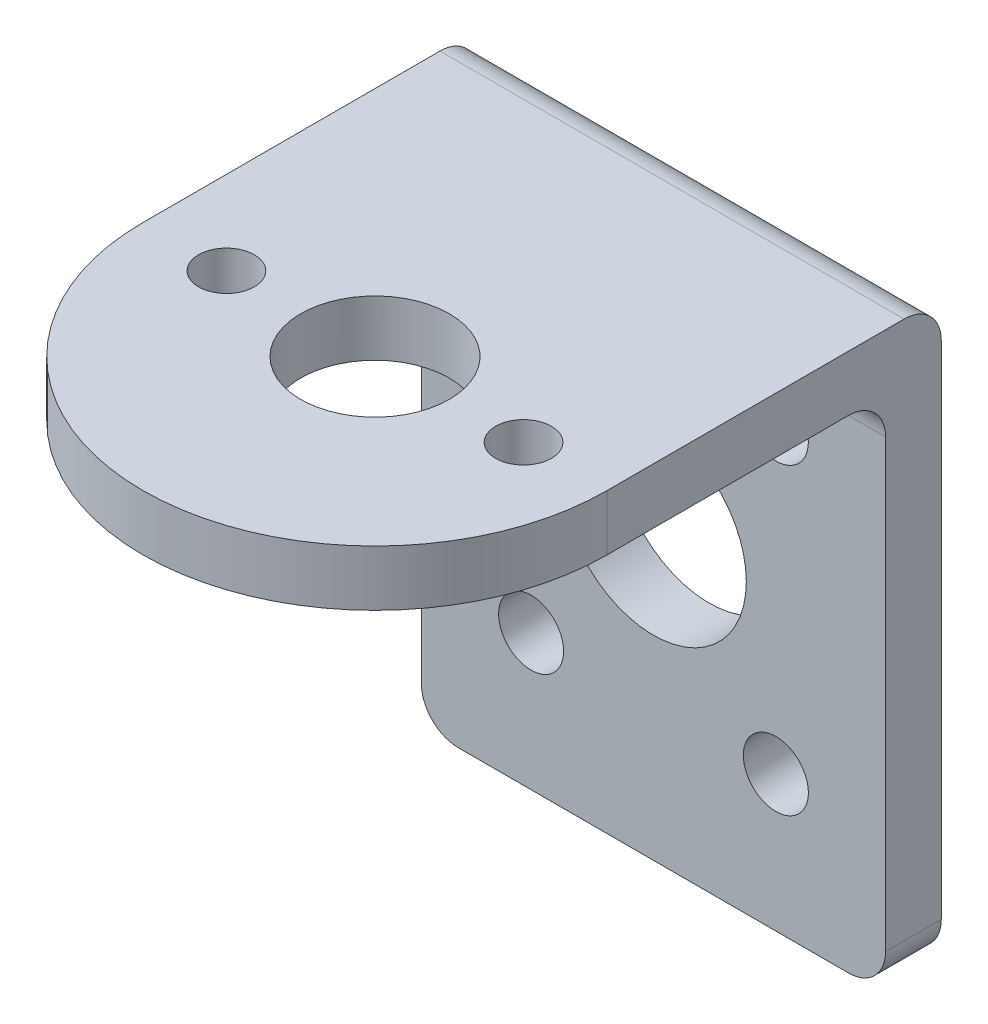
SolidWorks part; units mm, degrees
material "AISI 1020"
ref_plane "Plan de face" through (0, 0, 0) normal (0, 0, 1) x (1, 0, 0)
ref_plane "Plan de dessus" through (0, 0, 0) normal (0, 1, 0) x (1, 0, 0)
ref_plane "Plan de droite" through (0, 0, 0) normal (1, 0, 0) x (0, 0, -1)
sketch "Esquisse1" plane through (0, 0, 0) normal (0, 0, 1) x (1, 0, 0)
  line L0 (25, 15.4244) -> (0, -15.5756) construction
  line L1 (0, 15.4244) -> (25, 15.4244)
  line L2 (0, 15.4244) -> (0, -15.5756)
  line L3 (0, -15.5756) -> (25, -15.5756)
  line L4 (25, 15.4244) -> (25, -15.5756)
  line L5 (12.5, -0.0756) -> (12.5, 15.4244) construction
  line L6 (12.5, -0.0756) -> (0, -0.0756) construction
  circle A0 centre (12.5, -0.0756) radius 5
  circle A1 centre (19.0914, 8.0977) radius 1.75
  circle A2 centre (5.9086, 8.0977) radius 1.75
  circle A3 centre (19.0914, -8.249) radius 1.75
  circle A4 centre (5.9086, -8.249) radius 1.75
  dimension "D3" = 10
  dimension "D4" = 3.5
  dimension "D1" = 25
  dimension "D2" = 31
  dimension "D5" = 10.5
extrude "Boss.-Extru.1" add sketch "Esquisse1" along normal blind 3
sketch "Esquisse2" plane through (0, 0, 3) normal (0, 0, 1) x (1, 0, 0)
  line L0 (25, 15.4244) -> (0, 15.4244) construction
  line L1 (0, 15.4244) -> (25, 15.4244)
  line L2 (0, 15.4244) -> (0, 12.4244)
  line L3 (0, 12.4244) -> (25, 12.4244)
  line L4 (25, 15.4244) -> (25, 12.4244)
  line L5 (0, 15.4244) -> (0, -15.5756) construction
  dimension "D1" = 3
extrude "Boss.-Extru.2" add sketch "Esquisse2" along normal blind 30
sketch "Esquisse3" plane through (0, 12.4244, 0) normal (0, -1, 0) x (1, 0, 0)
  line L0 (0, 3) -> (25, 33) construction
  line L1 (12.5, 18) -> (23.0322, 18) construction
  line L2 (12.5, 18) -> (12.5, 25.9498) construction
  line L3 (0, 18.0005) -> (0, 33)
  line L4 (0, 33) -> (25, 33)
  line L5 (25, 33) -> (25, 18.0005)
  circle A0 centre (12.5, 18) radius 4
  circle A1 centre (20.5, 18) radius 1.5
  circle A2 centre (4.5, 18) radius 1.5
  arc A3 (0, 18.0005) -> (25, 18.0005) centre (12.5, 18.0005) cw
  dimension "D1" = 8
  dimension "D2" = 8
  dimension "D3" = 3
extrude "Enlèv. mat.-Extru.1" cut sketch "Esquisse3" against normal blind 30
fillet "Congé1" radius 2 4 edges at (25, -15.5756, 1.5) (0, -15.5756, 1.5) (12.5, 12.4244, 3) (12.5, 15.4244, 0)
